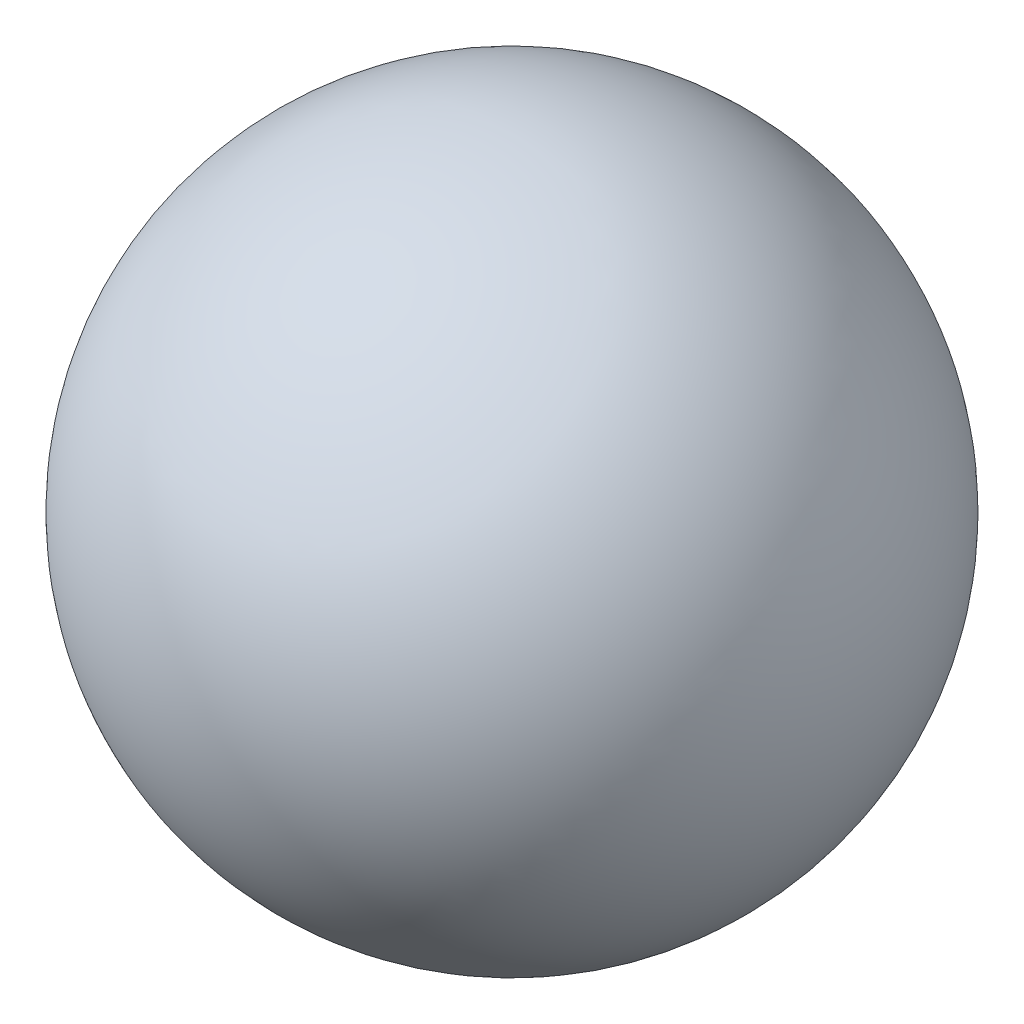
SolidWorks part; units mm, degrees
material "AISI 304"
ref_plane "Front" through (0, 0, 0) normal (0, 0, 1) x (1, 0, 0)
ref_plane "Top" through (0, 0, 0) normal (0, 1, 0) x (1, 0, 0)
ref_plane "Right" through (0, 0, 0) normal (1, 0, 0) x (0, 0, -1)
sketch "Sketch2" plane through (0, 0, 0) normal (0, 1, 0) x (1, 0, 0)
  line L0 (0, 0) -> (0, 8) construction
  line L1 (0, 7.5) -> (3.3833, 7.5) construction
  line L2 (1.9365, 7.5) -> (0, 7.5)
  line L3 (0, 7.5) -> (0, 0)
  line L4 (0, 4) -> (4, 4) construction
  arc A0 (0, 8) -> (0, 0) centre (0, 4) cw construction
  arc A1 (1.9365, 7.5) -> (0, 0) centre (0, 4) cw
  dimension "D1" = 8
  dimension "D2" = 0.5
revolve "Revolve1" add sketch "Sketch2" angle 360 about L3
hole_wizard "M3x0.5 Tapped Hole1" positions "Sketch3" profile "Sketch5" tap size "M3x0.5" standard "ANSI Metric"
sketch "Sketch3" plane through (0, 0, -7.5) normal (0, 0, -1) x (-1, 0, 0)
  point P3 (0, 0)
sketch "Sketch5" plane through (0, 0, -7.5) normal (1, 0, 0) x (0, 1, 0)
  line L0 (0, 0) -> (0, 5.7511)
  line L1 (0, 5.7511) -> (1.25, 5)
  line L2 (1.25, 5) -> (1.25, 0)
  line L5 (1.25, 0) -> (0, 0)
  line L10 (0, 5.7511) -> (-1.25, 5) construction
  line L11 (0, -6.35) -> (0, 107.95) construction
  dimension "Tap Drill Dia." = 2.5
  dimension "Tap Drill Depth" = 5
  dimension "Drill Angle" = 118
cosmetic thread "Hole Thread1" parameters "D1"=6, "D2"=3
